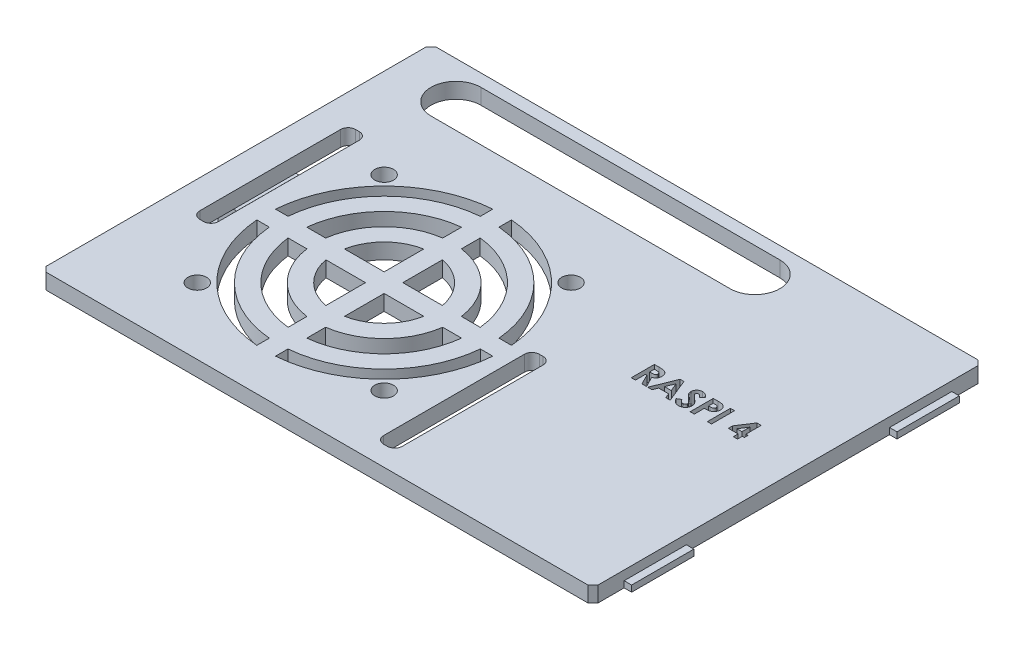
SolidWorks part; units mm, degrees
ref_plane "Front Plane" through (0, 0, 0) normal (0, 0, 1) x (1, 0, 0)
ref_plane "Top Plane" through (0, 0, 0) normal (0, 1, 0) x (1, 0, 0)
ref_plane "Right Plane" through (0, 0, 0) normal (1, 0, 0) x (0, 0, -1)
sketch "Sketch1" plane through (0, 0, 0) normal (0, 1, 0) x (1, 0, 0)
  line L0 (44.6906, 30.2082) -> (43.7764, 31.1224)
  line L1 (43.7764, 31.1224) -> (-43.3951, 31.1224)
  line L2 (-43.3951, 31.1224) -> (-44.3094, 30.2082)
  line L3 (-44.3094, 30.2082) -> (-44.3094, -30.9634)
  line L4 (-44.3094, -30.9634) -> (-43.3951, -31.8776)
  line L5 (-43.3951, -31.8776) -> (43.7764, -31.8776)
  line L6 (43.7764, -31.8776) -> (44.6906, -30.9634)
  line L7 (44.6906, -30.9634) -> (44.6906, 30.2082)
  dimension "D1" = 43.7764
  dimension "D2" = 43.7764
  dimension "D3" = 44.6906
  dimension "D4" = 44.6906
  dimension "D5" = 43.3951
  dimension "D6" = 43.3951
  dimension "D7" = 44.3094
  dimension "D8" = 44.3094
  dimension "D9" = 30.2082
  dimension "D10" = 30.2082
  dimension "D11" = 31.1224
  dimension "D12" = 31.1224
  dimension "D13" = 30.9634
  dimension "D14" = 30.9634
  dimension "D15" = 31.8776
  dimension "D16" = 31.8776
extrude "Boss-Extrude1" add sketch "Sketch1" along normal blind 2.5
sketch "Sketch2" plane through (0, 2.5, 0) normal (0, 1, 0) x (1, 0, 0)
  line L0 (43.6936, 30.9224) -> (-43.3123, 30.9224)
  line L1 (-43.3123, 30.9224) -> (-44.1094, 30.1253)
  line L2 (-44.1094, 30.1253) -> (-44.1094, -30.8805)
  line L3 (-44.1094, -30.8805) -> (-43.3123, -31.6776)
  line L4 (-43.3123, -31.6776) -> (43.6936, -31.6776)
  line L5 (43.6936, -31.6776) -> (44.4906, -30.8805)
  line L6 (44.4906, -30.8805) -> (44.4906, 30.1253)
  line L7 (44.4906, 30.1253) -> (43.6936, 30.9224)
  line L8 (44.6906, -30.9634) -> (44.6906, 30.2082)
  line L9 (44.6906, 30.2082) -> (43.7764, 31.1224)
  line L10 (43.7764, 31.1224) -> (-43.3951, 31.1224)
  line L11 (-43.3951, 31.1224) -> (-44.3094, 30.2082)
  line L12 (-44.3094, 30.2082) -> (-44.3094, -30.9634)
  line L13 (-44.3094, -30.9634) -> (-43.3951, -31.8776)
  line L14 (-43.3951, -31.8776) -> (43.7764, -31.8776)
  line L15 (43.7764, -31.8776) -> (44.6906, -30.9634)
  line L16 (44.6906, -30.9634) -> (44.6906, 30.2082)
  line L17 (44.6906, 30.2082) -> (43.7764, 31.1224)
  line L18 (43.7764, 31.1224) -> (-43.3951, 31.1224)
  line L19 (-43.3951, 31.1224) -> (-44.3094, 30.2082)
  line L20 (-44.3094, 30.2082) -> (-44.3094, -30.9634)
  line L21 (-44.3094, -30.9634) -> (-43.3951, -31.8776)
  line L22 (-43.3951, -31.8776) -> (43.7764, -31.8776)
  line L23 (43.7764, -31.8776) -> (44.6906, -30.9634)
  dimension "D1" = 0
  dimension "D2" = 0.2
extrude "Cut-Extrude1" cut sketch "Sketch2" against normal blind 2.5
sketch "Sketch4" plane through (44.4906, 0, 0) normal (1, 0, 0) x (0, 0, -1)
  line L0 (-30.8805, 0) -> (30.1253, 0) construction
  line L5 (30.9224, 0) -> (30.9224, 2.5) construction
  line L6 (-0.3776, 2.5) -> (-0.3776, 0) construction
  line L7 (-30.8805, 2.5) -> (30.1253, 2.5) construction
  line L8 (25.9224, 0) -> (15.9224, 0)
  line L9 (25.9224, 0) -> (25.9224, 1)
  line L10 (25.9224, 1) -> (15.9224, 1)
  line L11 (15.9224, 0) -> (15.9224, 1)
  line L12 (25.9224, 0) -> (15.9224, 1) construction
  line L13 (25.9224, 1) -> (15.9224, 0) construction
  line L14 (-26.6776, 1) -> (-16.6776, 0) construction
  line L15 (-26.6776, 0) -> (-16.6776, 1) construction
  line L16 (-16.6776, 0) -> (-16.6776, 1)
  line L17 (-26.6776, 1) -> (-16.6776, 1)
  line L18 (-26.6776, 0) -> (-26.6776, 1)
  line L19 (-26.6776, 0) -> (-16.6776, 0)
  point P11 (20.9224, 0.5)
  point P18 (-21.6776, 0.5)
  dimension "D1" = 1
  dimension "D2" = 10
  dimension "D3" = 10
extrude "Boss-Extrude2" add sketch "Sketch4" along normal blind 1.2
sketch "Sketch6" plane through (0, 0, 0) normal (0, -1, 0) x (1, 0, 0)
  line L0 (-44.1094, -30.1253) -> (-44.1094, 30.8805) construction
  line L1 (-42.0094, 5.3776) -> (-40.5094, 5.3776)
  line L2 (-42.0094, 5.3776) -> (-42.0094, -4.6224)
  line L3 (-42.0094, -4.6224) -> (-40.5094, -4.6224)
  line L4 (-40.5094, 5.3776) -> (-40.5094, -4.6224)
  line L5 (-42.0094, 5.3776) -> (-40.5094, -4.6224) construction
  line L6 (-42.0094, -4.6224) -> (-40.5094, 5.3776) construction
  point P4 (-41.2594, 0.3776)
  point P7 (-44.1094, 0.3776)
  dimension "D1" = 10
  dimension "D2" = 1.5
  dimension "D3" = 2.1
extrude "Boss-Extrude3" add sketch "Sketch6" along normal blind 5
sketch "Sketch7" plane through (-42.0094, 0, 0) normal (-1, 0, 0) x (0, 0, 1)
  line L0 (5.3776, -5) -> (5.3776, 0) construction
  line L1 (-4.6224, -5) -> (5.3776, -5)
  line L2 (-4.6224, -5) -> (-4.6224, -3.8)
  line L3 (-4.6224, -3.8) -> (5.3776, -3.8)
  line L4 (5.3776, -5) -> (5.3776, -3.8)
  line L5 (-4.6224, -5) -> (5.3776, -3.8) construction
  line L6 (-4.6224, -3.8) -> (5.3776, -5) construction
  point P4 (0.3776, -4.4)
  dimension "D1" = 1.2
extrude "Boss-Extrude4" add sketch "Sketch7" along normal blind 1.5
chamfer "Chamfer1" distance 1.5 angle 45 1 edges at (-40.5094, 0, 0.3776)
chamfer "Chamfer2" distance 0.5 angle 45 1 edges at (-42.0094, -3.8, 0.3776)
chamfer "Chamfer3" distance 0.2 angle 45 2 edges at (-43.5094, -5, 0.3776) (-43.5094, -3.8, 0.3776)
sketch "Sketch9" plane through (0, 0, 0) normal (0, -1, 0) x (1, 0, 0)
  line L0 (-34.1094, -24.9224) -> (13.8906, -24.9224) construction
  line L1 (7.7, 3.5) -> (8.3, 3.5)
  line L2 (6.5, 4.7) -> (6.5, 27.3)
  line L3 (7.7, 28.5) -> (8.3, 28.5)
  line L4 (9.5, 4.7) -> (9.5, 27.3)
  line L5 (6.5, 3.5) -> (9.5, 28.5) construction
  line L6 (6.5, 28.5) -> (9.5, 3.5) construction
  line L7 (-38.3, 12) -> (-37.7, 12)
  line L8 (-39.5, 10.8) -> (-39.5, -11.8)
  line L9 (-38.3, -13) -> (-37.7, -13)
  line L10 (-36.5, 10.8) -> (-36.5, -11.8)
  line L11 (-39.5, 12) -> (-36.5, -13) construction
  line L12 (-39.5, -13) -> (-36.5, 12) construction
  line L17 (-34.1094, -20.9224) -> (13.8906, -20.9224)
  line L18 (-34.1094, -28.9224) -> (13.8906, -28.9224)
  line L19 (-44.1094, -30.1253) -> (-44.1094, 30.8805) construction
  line L20 (43.6936, -30.9224) -> (-43.3123, -30.9224) construction
  arc A0 (-37.7, -13) -> (-36.5, -11.8) centre (-37.7, -11.8) ccw
  arc A1 (-39.5, -11.8) -> (-38.3, -13) centre (-38.3, -11.8) ccw
  arc A2 (-38.3, 12) -> (-39.5, 10.8) centre (-38.3, 10.8) ccw
  arc A3 (-36.5, 10.8) -> (-37.7, 12) centre (-37.7, 10.8) ccw
  arc A4 (7.7, 3.5) -> (6.5, 4.7) centre (7.7, 4.7) cw
  arc A5 (8.3, 3.5) -> (9.5, 4.7) centre (8.3, 4.7) ccw
  arc A6 (8.3, 28.5) -> (9.5, 27.3) centre (8.3, 27.3) cw
  arc A7 (6.5, 27.3) -> (7.7, 28.5) centre (7.7, 27.3) cw
  arc A9 (-34.1094, -20.9224) -> (-34.1094, -28.9224) centre (-34.1094, -24.9224) ccw
  arc A10 (13.8906, -28.9224) -> (13.8906, -20.9224) centre (13.8906, -24.9224) ccw
  point P4 (8, 16)
  point P9 (-38, -0.5)
  point P37 (-10.1094, -24.9224)
  dimension "D9" = 1.2
  dimension "D10" = 48
  dimension "D11" = 4
  dimension "D1" = 3
  dimension "D2" = 25
  dimension "D3" = 0.5
  dimension "D4" = 38
  dimension "D5" = 8
  dimension "D6" = 3
  dimension "D7" = 25
  dimension "D8" = 16
  dimension "D12" = 34
  dimension "D13" = 6
extrude "Cut-Extrude2" cut sketch "Sketch9" against normal blind 3
sketch "Sketch10" plane through (0, 2.5, 0) normal (0, 1, 0) x (1, 0, 0)
  line L0 (-14.7094, 13) -> (-14.7094, -25) construction
  line L1 (-34.7094, 14) -> (5.2906, 14) construction
  line L2 (-34.7094, 14) -> (-34.7094, -26) construction
  line L3 (-34.7094, -26) -> (5.2906, -26) construction
  line L4 (5.2906, 14) -> (5.2906, -26) construction
  line L5 (-34.7094, 14) -> (5.2906, -26) construction
  line L6 (-34.7094, -26) -> (5.2906, 14) construction
  line L7 (-33.7094, -6) -> (4.2906, -6) construction
  line L8 (-16.2094, 12.9407) -> (-16.2094, -24.9407)
  line L9 (-13.2094, -24.9407) -> (-13.2094, 12.9407)
  line L10 (-33.6501, -7.5) -> (4.2313, -7.5)
  line L11 (4.2313, -4.5) -> (-33.6501, -4.5)
  line L13 (-29.7094, -21) -> (0.2906, -21) construction
  line L14 (-29.7094, -21) -> (-29.7094, 9) construction
  line L15 (-29.7094, 9) -> (0.2906, 9) construction
  line L16 (0.2906, -21) -> (0.2906, 9) construction
  line L17 (-29.7094, -21) -> (0.2906, 9) construction
  line L18 (-29.7094, 9) -> (0.2906, -21) construction
  circle A0 centre (-14.7094, -6) radius 19
  circle A1 centre (-14.7094, -6) radius 17
  circle A2 centre (-14.7094, -6) radius 14
  circle A3 centre (-14.7094, -6) radius 11
  circle A4 centre (-14.7094, -6) radius 8
  circle A5 centre (0.2906, 9) radius 1.5
  circle A6 centre (-29.7094, 9) radius 1.5
  circle A7 centre (-29.7094, -21) radius 1.5
  circle A8 centre (0.2906, -21) radius 1.5
  point P4 (-14.7094, -6)
  dimension "D5" = 38
  dimension "D6" = 34
  dimension "D7" = 28
  dimension "D8" = 22
  dimension "D9" = 16
  dimension "D16" = 3
  dimension "D1" = 40
  dimension "D2" = 40
  dimension "D3" = 15
  dimension "D4" = 6
  dimension "D10" = 1.5
  dimension "D11" = 1.5
  dimension "D12" = 1.5
  dimension "D13" = 3
  dimension "D14" = 30
  dimension "D15" = 30
extrude "Cut-Extrude3" cut sketch "Sketch10" against normal blind 3 contours L11 A4 L9 | L9 A4 L10 | L10 A4 L8 | L8 A4 L11 | A3 L8 A2 L11 | A3 L11 A2 L9 | A3 L9 A2 L10 | A3 L10 A2 L8 | A1 L10 A0 L8 | A1 L8 A0 L11 | A1 L11 A0 L9 | A1 L9 A0 L10 | A7 | A8 | A6 | A5
sketch "Sketch11" plane through (0, 2.5, 0) normal (0, 1, 0) x (1, 0, 0)
  text T0 "RASPI 4" font "Century Gothic" height in points 14
extrude "Cut-Extrude4" cut sketch "Sketch11" against normal blind 2
